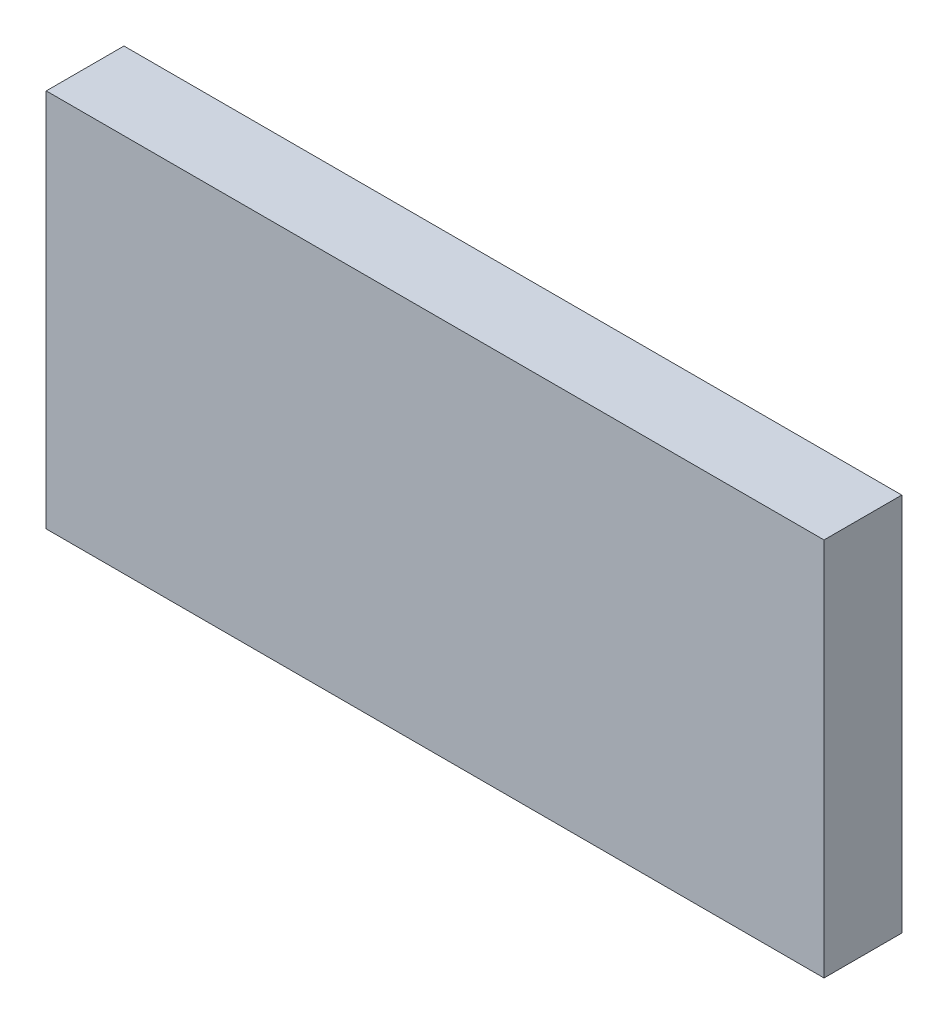
SolidWorks part; units mm, degrees
ref_plane "Front Plane" through (0, 0, 0) normal (0, 0, 1) x (1, 0, 0)
ref_plane "Top Plane" through (0, 0, 0) normal (0, 1, 0) x (1, 0, 0)
ref_plane "Right Plane" through (0, 0, 0) normal (1, 0, 0) x (0, 0, -1)
sketch "Sketch1" plane through (0, 0, 0) normal (0, 0, 1) x (1, 0, 0)
  line L0 (-5.005, 1.875) -> (5, 1.875)
  line L1 (5, 1.875) -> (5, -3.005)
  line L2 (5, -3.005) -> (-5.005, -3.005)
  line L3 (-5.005, -3.005) -> (-5.005, 1.875)
extrude "Component_Outline" add sketch "Sketch1" along normal blind 1 separate body
sketch3d "3DSketch1"
  line L0 (0, 0, 0) -> (1, 0, 0)
  line L1 (0, 0, 0) -> (0, 1, 0)
  line L2 (0, 0, 0) -> (0, 0, 1)
  point P0 (0, 0, 0)
